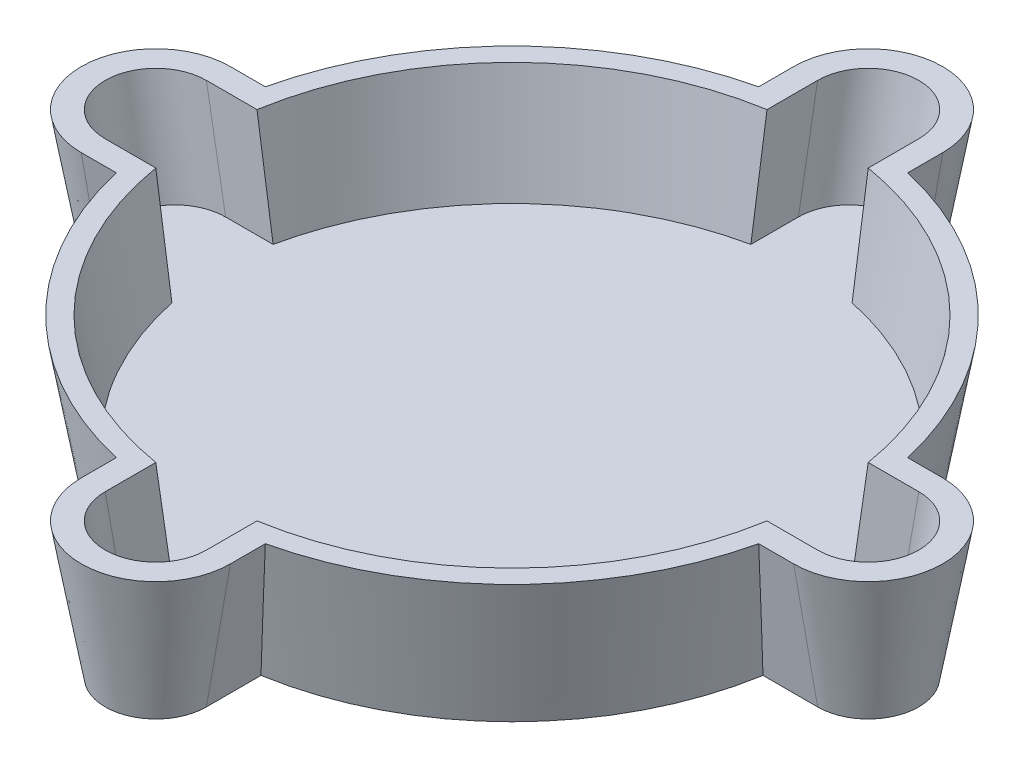
SolidWorks part; units mm, degrees
ref_plane "Front Plane" through (0, 0, 0) normal (0, 0, 1) x (1, 0, 0)
ref_plane "Top Plane" through (0, 0, 0) normal (0, 1, 0) x (1, 0, 0)
ref_plane "Right Plane" through (0, 0, 0) normal (1, 0, 0) x (0, 0, -1)
sketch "Sketch1" plane through (0, 0, 0) normal (0, 1, 0) x (1, 0, 0)
  line L0 (3.72, 26.21) -> (3.72, 22.1903)
  line L1 (-3.72, 26.21) -> (-3.72, 22.1903)
  line L2 (26.21, -3.72) -> (22.1903, -3.72)
  line L3 (26.21, 3.72) -> (22.1903, 3.72)
  line L4 (-3.72, -26.21) -> (-3.72, -22.1903)
  line L5 (3.72, -26.21) -> (3.72, -22.1903)
  line L6 (-26.21, 3.72) -> (-22.1903, 3.72)
  line L7 (-26.21, -3.72) -> (-22.1903, -3.72)
  arc A0 (-3.72, 22.1903) -> (-22.1903, 3.72) centre (0, 0) ccw
  arc A1 (3.72, 26.21) -> (-3.72, 26.21) centre (0, 26.21) ccw
  arc A2 (26.21, -3.72) -> (26.21, 3.72) centre (26.21, 0) ccw
  arc A3 (-3.72, -26.21) -> (3.72, -26.21) centre (0, -26.21) ccw
  arc A4 (-26.21, 3.72) -> (-26.21, -3.72) centre (-26.21, 0) ccw
  arc A5 (-22.1903, -3.72) -> (-3.72, -22.1903) centre (0, 0) ccw
  arc A6 (3.72, -22.1903) -> (22.1903, -3.72) centre (0, 0) ccw
  arc A7 (22.1903, 3.72) -> (3.72, 22.1903) centre (0, 0) ccw
  point P25 (0, 0)
  dimension "D1" = 22.5
  dimension "D2" = 26.21
  dimension "D3" = 3.72
  dimension "D4" = 4
extrude "Extrude-Thin1" add sketch "Sketch1" along normal blind 10 draft 10 thin
sketch "Sketch2" plane through (0, 0, 0) normal (0, -1, 0) x (1, 0, 0)
  line L8 (3.72, -26.21) -> (3.72, -22.1903)
  line L9 (22.1903, -3.72) -> (26.21, -3.72)
  line L10 (26.21, 3.72) -> (22.1903, 3.72)
  line L11 (3.72, 22.1903) -> (3.72, 26.21)
  line L12 (-3.72, 26.21) -> (-3.72, 22.1903)
  line L13 (-22.1903, 3.72) -> (-26.21, 3.72)
  line L14 (-26.21, -3.72) -> (-22.1903, -3.72)
  line L15 (-3.72, -22.1903) -> (-3.72, -26.21)
  line L16 (3.72, -26.21) -> (3.72, -22.1903)
  line L17 (22.1903, -3.72) -> (26.21, -3.72)
  line L18 (26.21, 3.72) -> (22.1903, 3.72)
  line L19 (3.72, 22.1903) -> (3.72, 26.21)
  line L20 (-3.72, 26.21) -> (-3.72, 22.1903)
  line L21 (-22.1903, 3.72) -> (-26.21, 3.72)
  line L22 (-26.21, -3.72) -> (-22.1903, -3.72)
  line L23 (-3.72, -22.1903) -> (-3.72, -26.21)
  arc A8 (-3.72, -26.21) -> (3.72, -26.21) centre (0, -26.21) ccw
  arc A9 (3.72, -22.1903) -> (22.1903, -3.72) centre (0, 0) ccw
  arc A10 (26.21, -3.72) -> (26.21, 3.72) centre (26.21, 0) ccw
  arc A11 (22.1903, 3.72) -> (3.72, 22.1903) centre (0, 0) ccw
  arc A12 (3.72, 26.21) -> (-3.72, 26.21) centre (0, 26.21) ccw
  arc A13 (-3.72, 22.1903) -> (-22.1903, 3.72) centre (0, 0) ccw
  arc A14 (-26.21, 3.72) -> (-26.21, -3.72) centre (-26.21, 0) ccw
  arc A15 (-22.1903, -3.72) -> (-3.72, -22.1903) centre (0, 0) ccw
  arc A16 (-3.72, -26.21) -> (3.72, -26.21) centre (0, -26.21) ccw
  arc A17 (3.72, -22.1903) -> (22.1903, -3.72) centre (0, 0) ccw
  arc A18 (26.21, -3.72) -> (26.21, 3.72) centre (26.21, 0) ccw
  arc A19 (22.1903, 3.72) -> (3.72, 22.1903) centre (0, 0) ccw
  arc A20 (3.72, 26.21) -> (-3.72, 26.21) centre (0, 26.21) ccw
  arc A21 (-3.72, 22.1903) -> (-22.1903, 3.72) centre (0, 0) ccw
  arc A22 (-26.21, 3.72) -> (-26.21, -3.72) centre (-26.21, 0) ccw
  arc A23 (-22.1903, -3.72) -> (-3.72, -22.1903) centre (0, 0) ccw
  dimension "D1" = 0
extrude "Boss-Extrude1" add sketch "Sketch2" against normal blind 2
sketch "Sketch5" plane through (0, 0, 0) normal (0, 0, 1) x (1, 0, 0)
  line L0 (31.6933, 10) -> (29.93, 0)
  line L1 (31.6933, 10) -> (29.93, 0)
sketch "Sketch4" plane through (0, 10, 0) normal (0, 1, 0) x (1, 0, 0)
  line L0 (26.21, 3.7233) -> (18.9035, 3.7233)
  line L1 (26.21, -3.7233) -> (18.9035, -3.7233)
  arc A0 (26.21, -3.7233) -> (26.21, 3.7233) centre (26.21, 0) ccw
  arc A1 (26.21, -5.4833) -> (26.21, 5.4833) centre (26.21, 0) ccw construction
  arc A3 (19.2606, 0.4867) -> (0.4867, 19.2606) centre (0, 0) ccw construction
  arc A5 (18.9035, -3.7233) -> (18.9035, 3.7233) centre (0, 0) ccw
  dimension "D1" = 1.76
extrude "Cut-Extrude1" cut sketch "Sketch4" along direction (-0.1736, -0.9848, 0) on the side against the normal up to surface (8 mm away)
pattern_circular "CirPattern1" count 4 over 360 about axis through (0, 0, 0) along (0, -1, 0) of "Cut-Extrude1"
ref_plane "Plane1" through (0, 0, 0) normal (0.7071, 0, 0.7071) x (0.7071, 0, -0.7071)
sketch "Sketch8" plane through (0, 0, 0) normal (0.7071, 0, 0.7071) x (0.7071, 0, -0.7071)
  line L0 (24.2633, 10) -> (22.5, 0)
  line L1 (24.2633, 10) -> (22.5, 0)
sketch "Sketch7" plane through (0, 10, 0) normal (0, 1, 0) x (1, 0, 0)
  line L0 (3.7233, 18.9035) -> (3.7233, 26.21) construction
  line L1 (26.21, 3.7233) -> (18.9035, 3.7233) construction
  line L2 (3.7233, 18.9035) -> (3.7233, 22.4871)
  line L3 (22.4871, 3.7233) -> (18.9035, 3.7233)
  arc A1 (18.9035, 3.7233) -> (3.7233, 18.9035) centre (0, 0) ccw construction
  arc A2 (22.2036, 5.1511) -> (5.1511, 22.2036) centre (0, 0) ccw
  arc A3 (22.4871, 3.7233) -> (3.7233, 22.4871) centre (0, 0) ccw
  arc A4 (18.9035, 3.7233) -> (3.7233, 18.9035) centre (0, 0) ccw
  dimension "D1" = 1.47
extrude "Cut-Extrude2" cut sketch "Sketch7" along direction (-0.1228, -0.9848, 0.1228) on the side against the normal up to surface (8 mm away)
pattern_circular "CirPattern2" count 4 over 360 of "Cut-Extrude2"
